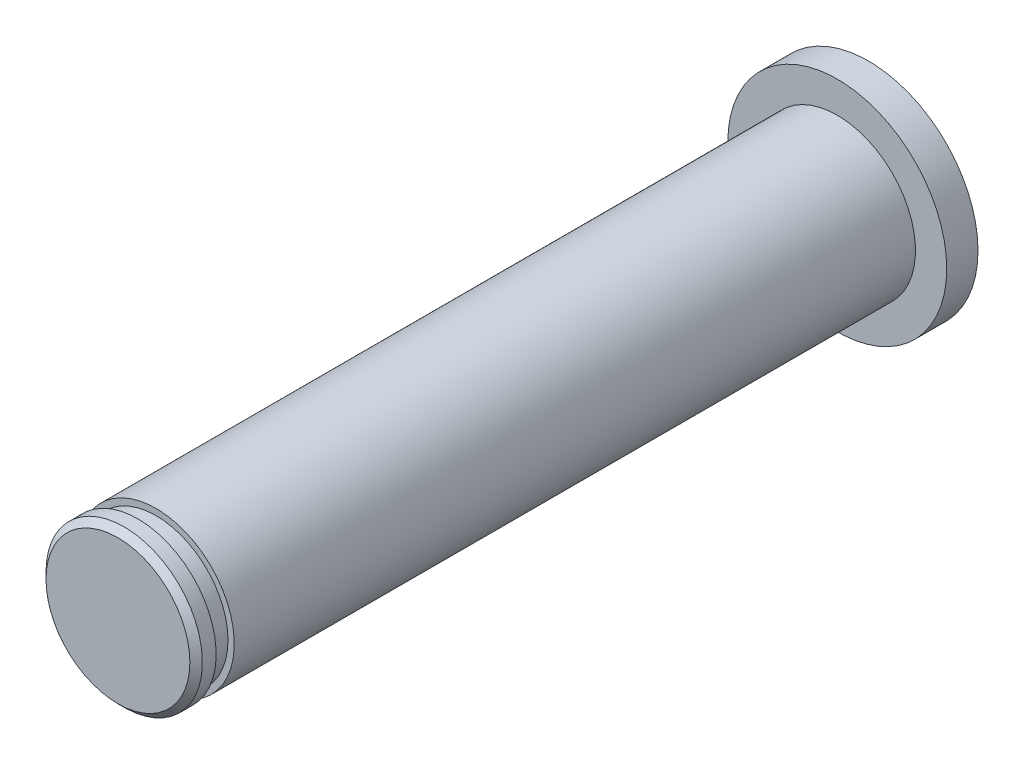
SolidWorks part; units mm, degrees
ref_plane "Front Plane" through (0, 0, 0) normal (0, 0, 1) x (1, 0, 0)
ref_plane "Top Plane" through (0, 0, 0) normal (0, 1, 0) x (1, 0, 0)
ref_plane "Right Plane" through (0, 0, 0) normal (1, 0, 0) x (0, 0, -1)
sketch "Sketch1" plane through (0, 0, 0) normal (0, 0, 1) x (1, 0, 0)
  circle A0 centre (0, 0) radius 4.445
extrude "Boss-Extrude1" add sketch "Sketch1" along normal blind 1.27
sketch "Sketch2" plane through (0, 0, 1.27) normal (0, 0, 1) x (1, 0, 0)
  circle A0 centre (0, 0) radius 3.175
extrude "Boss-Extrude2" add sketch "Sketch2" along normal blind 29.21
sketch "Sketch4" plane through (0, 0, 30.48) normal (0, 0, 1) x (1, 0, 0)
  circle A0 centre (0, 0) radius 2.921
  circle A1 centre (0, 0) radius 3.175
extrude "Cut-Extrude1" cut sketch "Sketch4" against normal blind 0.7366 from offset 0.8128 offset against normal yes
chamfer "Chamfer1" distance 0.254 angle 45 1 edges at (3.175, 0, 30.48)
